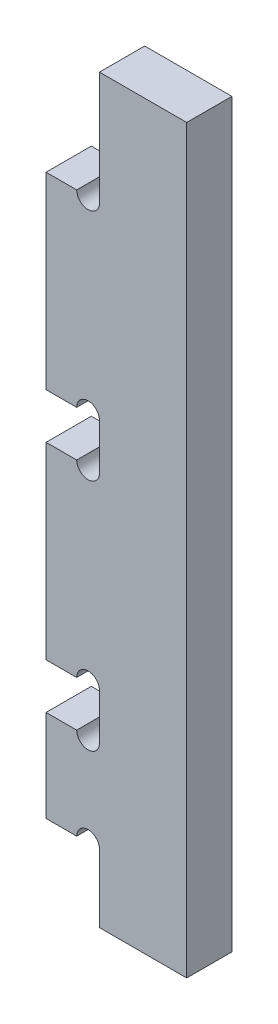
SolidWorks part; units mm, degrees
ref_plane "Front Plane" through (0, 0, 0) normal (0, 0, 1) x (1, 0, 0)
ref_plane "Top Plane" through (0, 0, 0) normal (0, 1, 0) x (1, 0, 0)
ref_plane "Right Plane" through (0, 0, 0) normal (1, 0, 0) x (0, 0, -1)
sketch "Sketch1" plane through (0, 0, 0) normal (0, 0, 1) x (1, 0, 0)
  line L0 (0, 0) -> (210.5, 0) construction
  line L1 (210.5, 0) -> (210.5, 170) construction
  line L2 (210.5, 170) -> (0, 170) construction
  line L3 (0, 170) -> (0, 0) construction
  line L4 (210.5, 0) -> (250, 0) construction
  line L5 (250, 0) -> (250, 170) construction
  line L6 (250, 170) -> (210.5, 170) construction
  line L7 (210.5, 170) -> (210.5, 0)
  line L8 (219.1, 0) -> (210.5, 0)
  line L9 (225.5, 0) -> (225.5, -19.05)
  line L10 (225.5, -19.05) -> (250, -19.05)
  line L11 (250, -19.05) -> (250, 0)
  line L12 (219.1, 170) -> (210.5, 170)
  line L13 (225.5, 170) -> (225.5, 189.05)
  line L14 (225.5, 189.05) -> (250, 189.05)
  line L15 (250, 189.05) -> (250, 170)
  line L16 (250, 170) -> (250, 0)
  arc A0 (219.1, 170) -> (225.5, 170) centre (222.3, 170) ccw
  arc A1 (225.5, 0) -> (219.1, 0) centre (222.3, 0) ccw
  dimension "D7" = 6.4
  dimension "D1" = 421
  dimension "D2" = 170
  dimension "D3" = 19.05
  dimension "D4" = 19.05
  dimension "D5" = 15
  dimension "D6" = 39.5
extrude "Boss-Extrude1" add sketch "Sketch1" along normal blind 12.7
sketch "Sketch2" plane through (0, 0, 12.7) normal (0, 0, 1) x (1, 0, 0)
  line L0 (219.1, 170) -> (210.5, 170) construction
  line L1 (210.5, 170) -> (210.5, 0) construction
  line L2 (210.5, 85) -> (250, 85) construction
  line L3 (250, -19.05) -> (250, 189.05) construction
  line L5 (210.5, 163.6) -> (225.5, 163.6) construction
  line L6 (225.5, 163.6) -> (225.5, 189.05) construction
  line L7 (210.5, 157.2) -> (225.5, 157.2) construction
  line L8 (210.5, 170) -> (225.5, 170) construction
  line L9 (210.5, 157.2) -> (210.5, 170)
  line L10 (225.5, 157.2) -> (225.5, 170)
  line L11 (210.5, 170) -> (219.1, 170)
  line L12 (210.5, 157.2) -> (219.1, 157.2)
  arc A0 (225.5, 170) -> (219.1, 170) centre (222.3, 170) ccw
  arc A1 (219.1, 157.2) -> (225.5, 157.2) centre (222.3, 157.2) ccw
  dimension "D3" = 6.4
  dimension "D1" = 6.4
  dimension "D2" = 6.4
extrude "Cut-Extrude1" cut sketch "Sketch2" against normal through all
pattern_linear "LPattern1" count 3 spacing 65.7 along (0, -1, 0) of "Cut-Extrude1"
